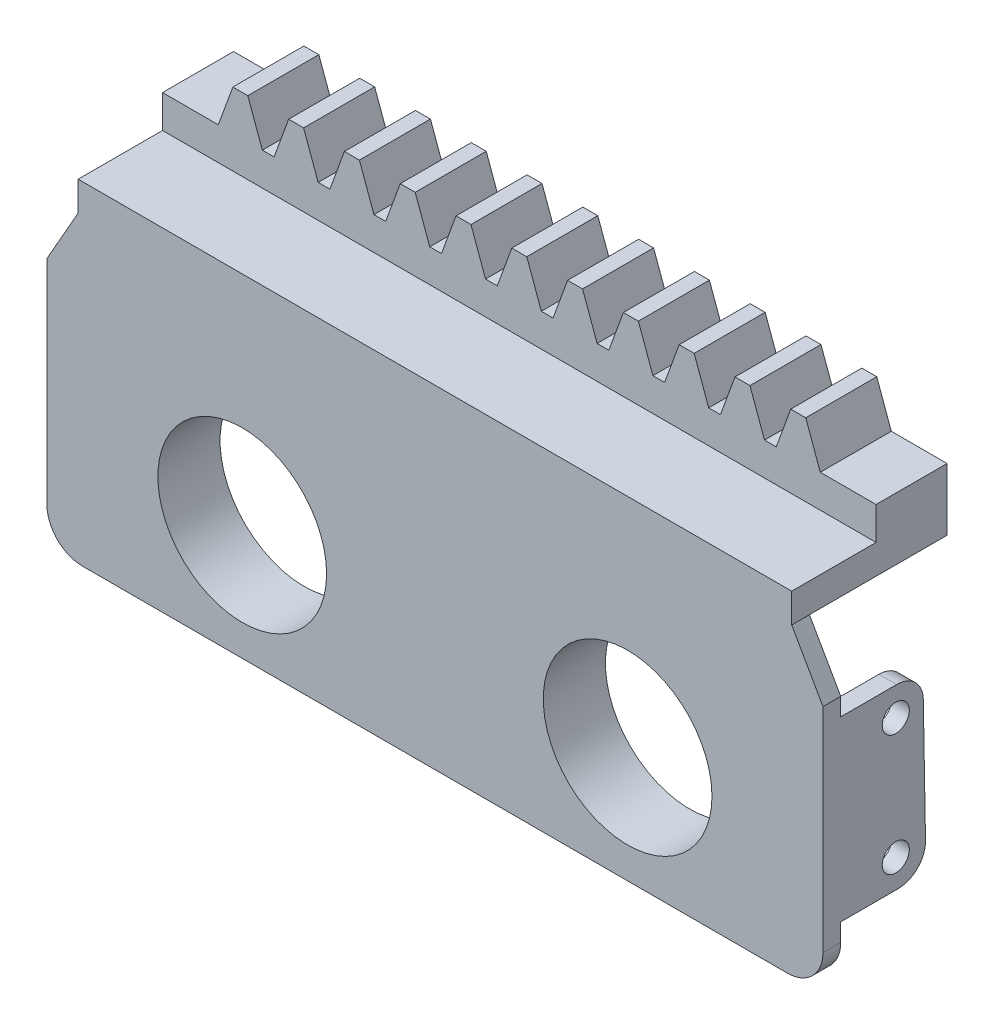
SolidWorks part; units mm, degrees
material "6061 合金"
ref_plane "Front" through (0, 0, 0) normal (0, 0, 1) x (1, 0, 0)
ref_plane "Top" through (0, 0, 0) normal (0, 1, 0) x (1, 0, 0)
ref_plane "Right" through (0, 0, 0) normal (1, 0, 0) x (0, 0, -1)
sketch "Sketch1" plane through (0, 0, 0) normal (0, 0, 1) x (1, 0, 0)
  line L1 (0, 0) -> (213.6283, 0)
  line L2 (0, 0) -> (0, -8)
  line L3 (0, -8) -> (213.6283, -8)
  line L4 (213.6283, 0) -> (213.6283, -8)
  dimension "D1" = 8
  dimension "L" = 213.6283
extrude "Extrude1" add sketch "Sketch1" along normal blind 8
sketch "Sketch2" plane through (0, 0, 8) normal (0, 0, 1) x (1, 0, 0)
  line L0 (0, 0) -> (1.6379, 4.5)
  line L1 (1.6379, 4.5) -> (3.3236, 4.5)
  line L2 (3.3236, 4.5) -> (4.9614, 0)
  line L3 (213.6283, 0) -> (0, 0) construction
  line L4 (0, 0) -> (4.9614, 0)
  line L5 (0.9099, 2.5) -> (4.0515, 2.5) construction
  dimension "alpha2" = 70
  dimension "alpha" = 110
  dimension "ha" = 2
  dimension "hf" = 2.5
  dimension "S" = 3.1416
extrude "Extrude2" add sketch "Sketch2" against normal up to surface (8 mm away) up to face at (106.8142, -4, 0)
pattern_linear "LPattern1" count 34 spacing 6.2832 along (1, 0, 0) of "Extrude2"
sketch "草图1" plane through (0, 0, 0) normal (0, 1, 0) x (1, 0, 0)
  line L1 (80.3597, 0) -> (213.6283, 0)
  line L2 (80.3597, 0) -> (80.3597, -8)
  line L3 (80.3597, -8) -> (213.6283, -8)
  line L4 (213.6283, 0) -> (213.6283, -8)
extrude "切除-拉伸1" cut sketch "草图1" against normal mid plane 50
sketch "草图2" plane through (0, 0, 0) normal (0, 1, 0) x (1, 0, 0)
  line L1 (75.3982, 0) -> (80.3597, 0)
  line L2 (75.3982, 0) -> (75.3982, -8)
  line L3 (75.3982, -8) -> (80.3597, -8)
  line L4 (80.3597, 0) -> (80.3597, -8)
  line L5 (0, 0) -> (4.9614, 0)
  line L6 (0, 0) -> (0, -8)
  line L7 (0, -8) -> (4.9614, -8)
  line L8 (4.9614, 0) -> (4.9614, -8)
extrude "切除-拉伸2" cut sketch "草图2" along normal blind 50
sketch "草图3" plane through (0, 0, 0) normal (0, 0, -1) x (-1, 0, 0)
  line L1 (-80.3597, -8) -> (0, -8)
  line L2 (-80.3597, -8) -> (-80.3597, -7)
  line L3 (-80.3597, -7) -> (0, -7)
  line L4 (0, -8) -> (0, -7)
  line L5 (-6.2832, 0) -> (0, 0) construction
  point P7 (0, -8)
  dimension "D1" = 7
extrude "切除-拉伸3" cut sketch "草图3" against normal blind 50
sketch "草图4" plane through (0, -7, 0) normal (0, -1, 0) x (1, 0, 0)
  line L1 (0, 8) -> (80.3597, 8)
  line L2 (0, 8) -> (0, 17.5)
  line L3 (0, 17.5) -> (80.3597, 17.5)
  line L4 (80.3597, 8) -> (80.3597, 17.5)
  point P5 (80.3597, 8)
  dimension "D1" = 9.5
extrude "凸台-拉伸1" add sketch "草图4" against normal blind 3.3
sketch "草图5" plane through (0, 0, 17.5) normal (0, 0, 1) x (1, 0, 0)
  line L0 (40.1798, -7) -> (40.1798, -28.2) construction
  line L1 (80.3597, -7) -> (0, -7) construction
  line L2 (18.4798, -28.2) -> (61.8798, -28.2) construction
  circle A0 centre (61.8798, -28.2) radius 10.5
  circle A1 centre (18.4798, -28.2) radius 10.5
  circle A2 centre (18.4798, -28.2) radius 9.5
  circle A3 centre (61.8798, -28.2) radius 9.5
  point P7 (40.1798, -28.2)
  dimension "D3" = 21
  dimension "D4" = 19
  dimension "D1" = 43.4
  dimension "D2" = 21.2
extrude "凸台-拉伸2" add sketch "草图5" against normal blind 7 separate body
sketch "草图6" plane through (0, 0, 17.5) normal (0, 0, 1) x (1, 0, 0)
  line L0 (40.1798, -7) -> (40.1798, -41.2) construction
  line L1 (80.3597, -7) -> (0, -7) construction
  line L2 (-3.5202, -41.2) -> (83.8798, -41.2)
  line L3 (-3.5202, -41.2) -> (-3.5202, -13.2)
  line L4 (-3.5202, -13.2) -> (0, -7)
  line L5 (0, -7) -> (80.3597, -7)
  line L6 (80.3597, -7) -> (83.8798, -13.2)
  line L7 (83.8798, -13.2) -> (83.8798, -41.2)
  circle A0 centre (18.4798, -28.2) radius 9.5 construction
  circle A1 centre (61.8798, -28.2) radius 10.5 construction
  circle A2 centre (18.4798, -28.2) radius 10.5 construction
  circle A3 centre (61.8798, -28.2) radius 10.5
  circle A4 centre (18.4798, -28.2) radius 10.5
  point P7 (40.1798, -41.2)
  dimension "D2" = 13
  dimension "D1" = 87.4
  dimension "D3" = 28
extrude "凸台-拉伸3" add sketch "草图6" against normal blind 2
sketch "草图7" plane through (-3.5202, 0, 0) normal (-1, 0, 0) x (0, 0, 1)
  line L0 (14.3, -15.2) -> (9.1986, -15.2) construction
  line L1 (17.5, -15.2) -> (9.1986, -15.2)
  line L2 (9.05, -35.2) -> (14.3, -35.2) construction
  line L3 (9.05, -35.2) -> (17.5, -35.2)
  line L4 (6.1991, -18.1464) -> (5.9505, -32.0446)
  line L7 (17.5, -13.2) -> (17.5, -41.2) construction
  line L8 (17.5, -35.2) -> (17.5, -15.2)
  arc A0 (9.1986, -15.2) -> (6.6261, -16.6565) centre (9.1986, -18.2) ccw construction
  arc A1 (9.1986, -15.2) -> (6.1991, -18.1464) centre (9.1986, -18.2) ccw
  arc A2 (6.57, -33.96) -> (8.6236, -35.1705) centre (9.05, -32.1) ccw construction
  arc A3 (8.6236, -35.1705) -> (9.05, -35.2) centre (9.05, -32.1) ccw construction
  arc A4 (10.6707, -16.6601) -> (7.9293, -20.1399) centre (9.3, -18.4) ccw
  arc A5 (7.9293, -20.1399) -> (10.6707, -16.6601) centre (9.3, -18.4) ccw
  arc A6 (10.6707, -16.6601) -> (7.9293, -20.1399) centre (9.3, -18.4) ccw construction
  arc A7 (7.9293, -20.1399) -> (10.6707, -16.6601) centre (9.3, -18.4) ccw construction
  arc A8 (10.5164, -30.1489) -> (8.0836, -33.8511) centre (9.3, -32) ccw
  arc A9 (8.0836, -33.8511) -> (10.5164, -30.1489) centre (9.3, -32) ccw
  arc A10 (10.5164, -30.1489) -> (8.0836, -33.8511) centre (9.3, -32) ccw construction
  arc A11 (8.0836, -33.8511) -> (10.5164, -30.1489) centre (9.3, -32) ccw construction
  arc A12 (5.9505, -32.0446) -> (8.6236, -35.1705) centre (9.05, -32.1) ccw
  arc A13 (8.6236, -35.1705) -> (9.05, -35.2) centre (9.05, -32.1) ccw
  dimension "D1" = 0
  dimension "D2" = 0
extrude "凸台-拉伸4" add sketch "草图7" against normal blind 2
ref_plane "基准面1" through (40.1798, 0, 0) normal (-1, 0, 0) x (0, 0, 1)
mirror "镜向1" about plane through (40.1798, 0, 0) normal (-1, 0, 0) of "凸台-拉伸4"
sketch "草图8" plane through (-3.5202, 0, 0) normal (-1, 0, 0) x (0, 0, 1)
  arc A0 (9.3, -30.4) -> (9.3, -33.6) centre (9.3, -32) ccw construction
  arc A1 (9.3, -16.8) -> (9.3, -20) centre (9.3, -18.4) ccw construction
  arc A2 (9.3, -30.4) -> (9.3, -33.6) centre (9.3, -32) ccw construction
  arc A3 (9.3, -16.8) -> (9.3, -20) centre (9.3, -18.4) ccw construction
  circle A4 centre (9.3, -18.4) radius 1.525
  circle A5 centre (9.3, -32) radius 1.525
  dimension "D1" = 3.05
extrude "切除-拉伸4" cut sketch "草图8" against normal blind 2
mirror "镜向2" about plane through (40.1798, 0, 0) normal (-1, 0, 0) of "切除-拉伸4"
fillet "圆角1" radius 4 2 edges at (83.8798, -41.2, 16.5) (-3.5202, -41.2, 16.5)
sketch "草图9" plane through (0, -3.7, 0) normal (0, 1, 0) x (1, 0, 0)
  circle A0 centre (120.7688, -15) radius 1.2 construction
  circle A1 centre (120.7688, -15) radius 1.2
  circle A2 centre (135.7688, -15) radius 1.2
  circle A3 centre (150.7688, -15) radius 1.2
  circle A4 centre (165.7688, -15) radius 1.2
  circle A5 centre (180.7688, -15) radius 1.2
  dimension "D2" = 15
  dimension "D1" = 5
hole_wizard "M2 螺纹孔1" [suppressed] positions "草图10" profile "草图11" tap size "M2" standard "GB"
sketch "草图10" plane through (0, -3.7, 0) normal (0, 1, 0) x (1, 0, 0)
  point P0 (-633.5377, -15)
  point P3 (-618.5377, -15)
  point P6 (-603.5377, -15)
  point P9 (-588.5377, -15)
  point P12 (-573.5377, -15)
sketch "草图11" plane through (-633.5377, -3.7, 15) normal (1, 0, 0) x (0, 0, 1)
  line L0 (0, 0) -> (0, 5.6807)
  line L1 (0, 5.6807) -> (0.8, 5.2)
  line L2 (0.8, 5.2) -> (0.8, 0)
  line L5 (0.8, 0) -> (0, 0)
  line L10 (0, 5.6807) -> (-0.8, 5.2) construction
  line L11 (0, -6.35) -> (0, 107.95) construction
  dimension "螺纹孔钻头直径" = 1.6
  dimension "螺纹孔钻头深度" = 5.2
  dimension "导头角度" = 118
sketch "草图14" plane through (0, 0, 17.5) normal (0, 0, 1) x (1, 0, 0)
  line L0 (-3.5202, -13.2) -> (-3.5202, -37.2) construction
  line L1 (-3.5202, -15.2) -> (-1.5202, -15.2)
  line L2 (-3.5202, -15.2) -> (-3.5202, -35.2)
  line L3 (-3.5202, -35.2) -> (-1.5202, -35.2)
  line L4 (-1.5202, -15.2) -> (-1.5202, -35.2)
  line L5 (-1.5202, -15.2) -> (-3.5202, -15.2) construction
  line L6 (-3.5202, -35.2) -> (-1.5202, -35.2) construction
  dimension "D1" = 2
extrude "凸台-拉伸5" [suppressed] add sketch "草图14" along normal blind 8
mirror "镜向3" [suppressed] about plane through (40.1798, 0, 0) normal (-1, 0, 0)
